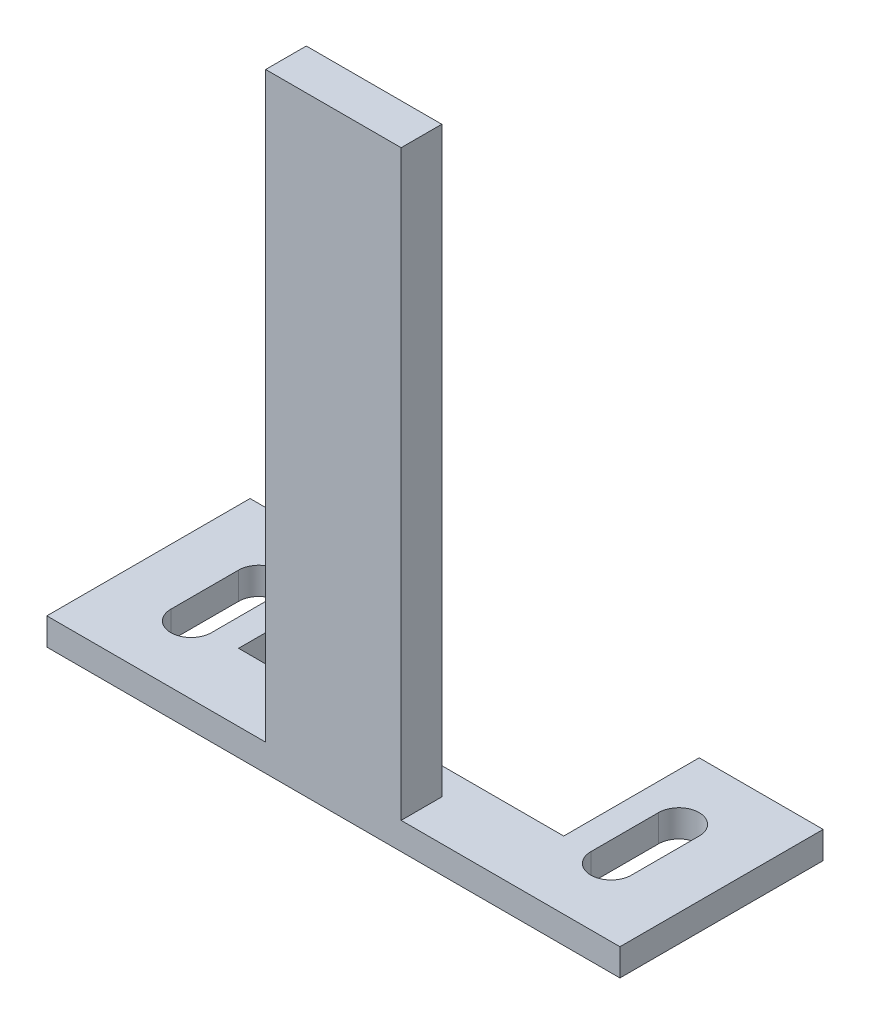
SolidWorks part; units mm, degrees
ref_plane "Płaszczyzna przednia" through (0, 0, 0) normal (0, 0, 1) x (1, 0, 0)
ref_plane "Płaszczyzna górna" through (0, 0, 0) normal (0, 1, 0) x (1, 0, 0)
ref_plane "Płaszczyzna prawa" through (0, 0, 0) normal (1, 0, 0) x (0, 0, -1)
sketch "Szkic1" plane through (0, 0, 0) normal (0, 1, 0) x (1, 0, 0)
  line L0 (0, 7.5) -> (0, -7.5) construction
  line L1 (-21.15, 7.5) -> (-12, 7.5)
  line L2 (-21.15, 7.5) -> (-21.15, -7.5)
  line L3 (-21.15, -7.5) -> (21.15, -7.5)
  line L4 (21.15, 7.5) -> (21.15, -7.5)
  line L5 (-21.15, 7.5) -> (21.15, -7.5) construction
  line L6 (-21.15, -7.5) -> (21.15, 7.5) construction
  line L7 (-15.5, 2.5) -> (-15.5, -2.5) construction
  line L8 (-14, 2.5) -> (-14, -2.5)
  line L9 (-17, 2.5) -> (-17, -2.5)
  line L10 (15.5, 2.5) -> (15.5, -2.5) construction
  line L11 (17, 2.5) -> (17, -2.5)
  line L12 (14, 2.5) -> (14, -2.5)
  line L13 (12, 7.5) -> (12, -2.5)
  line L14 (12, -2.5) -> (-12, -2.5)
  line L15 (-12, -2.5) -> (-12, 7.5)
  line L16 (12, 7.5) -> (21.15, 7.5)
  arc A3 (-14, 2.5) -> (-17, 2.5) centre (-15.5, 2.5) ccw
  arc A4 (-17, -2.5) -> (-14, -2.5) centre (-15.5, -2.5) ccw
  arc A5 (17, 2.5) -> (14, 2.5) centre (15.5, 2.5) ccw
  arc A6 (14, -2.5) -> (17, -2.5) centre (15.5, -2.5) ccw
  point P0 (0, 0)
  point P10 (-15.5, 0)
  point P18 (15.5, 0)
  dimension "D3" = 5
  dimension "D4" = 1.5
  dimension "D1" = 42.3
  dimension "D2" = 15
  dimension "D5" = 31
  dimension "D6" = 5
  dimension "D7" = 24
extrude "Dodanie-wyciągnięcie1" add sketch "Szkic1" along normal blind 2
sketch "Szkic4" plane through (0, 0, 7.5) normal (0, 0, 1) x (1, 0, 0)
  line L0 (0, 45) -> (0, 0) construction
  line L1 (5, 0) -> (-5, 0)
  line L2 (5, 0) -> (5, 45)
  line L3 (5, 45) -> (-5, 45)
  line L4 (-5, 0) -> (-5, 45)
  line L5 (-21.15, 0) -> (21.15, 0) construction
  point P4 (0, 0)
  point P8 (0, 0)
  point P9 (0, 0)
  dimension "D1" = 45
  dimension "D6" = 10
extrude "Dodanie-wyciągnięcie2" add sketch "Szkic4" against normal blind 3
